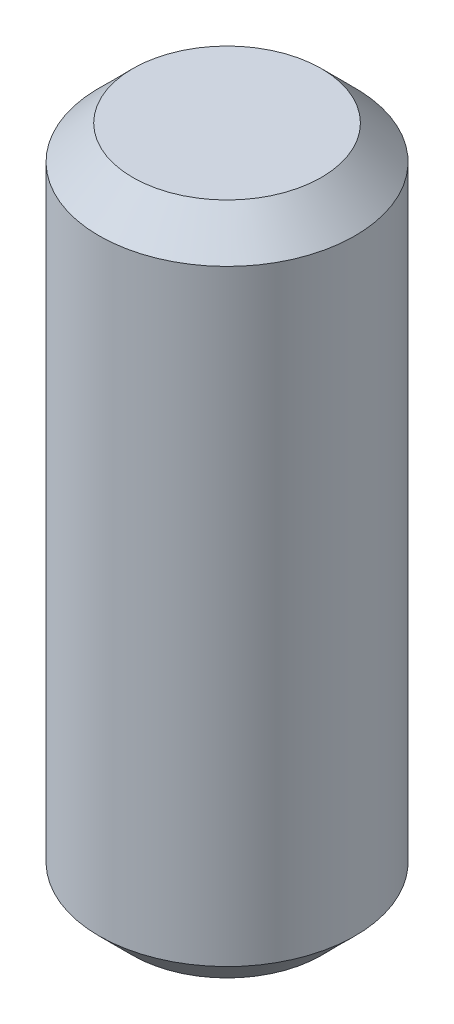
SolidWorks part; units mm, degrees
ref_plane "Front Plane" through (0, 0, 0) normal (0, 0, 1) x (1, 0, 0)
ref_plane "Top Plane" through (0, 0, 0) normal (0, 1, 0) x (1, 0, 0)
ref_plane "Right Plane" through (0, 0, 0) normal (1, 0, 0) x (0, 0, -1)
sketch "Sketch1" plane through (0, 0, 0) normal (0, 1, 0) x (1, 0, 0)
  circle A0 centre (0, 0) radius 1.9
  dimension "D1" = 3.8
extrude "Boss-Extrude1" add sketch "Sketch1" along normal blind 10
chamfer "Chamfer1" distance 0.5 angle 45 1 edges at (0, 0, 1.9)
chamfer "Chamfer2" distance 0.5 angle 45 1 edges at (0, 10, 1.9)
